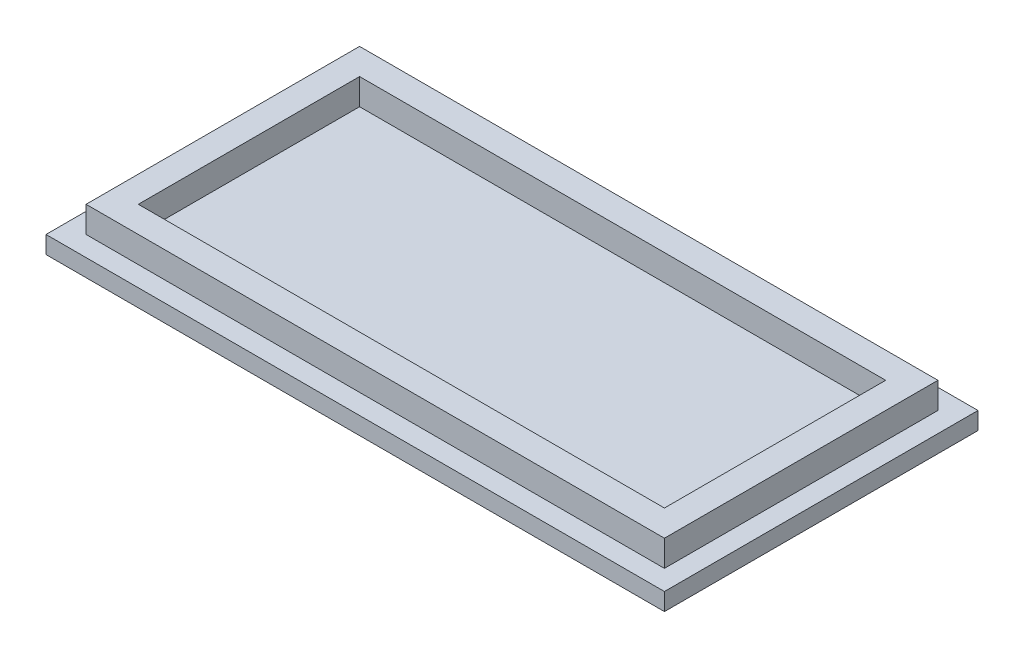
SolidWorks part; units mm, degrees
ref_plane "Piano frontale" through (0, 0, 0) normal (0, 0, 1) x (1, 0, 0)
ref_plane "Piano superiore" through (0, 0, 0) normal (0, 1, 0) x (1, 0, 0)
ref_plane "Piano destro" through (0, 0, 0) normal (1, 0, 0) x (0, 0, -1)
sketch "Schizzo1" plane through (0, 0, 0) normal (0, 1, 0) x (1, 0, 0)
  line L1 (-35.5, -18) -> (35.5, -18)
  line L2 (-35.5, -18) -> (-35.5, 18)
  line L3 (-35.5, 18) -> (35.5, 18)
  line L4 (35.5, -18) -> (35.5, 18)
  line L5 (-35.5, -18) -> (35.5, 18) construction
  line L6 (-35.5, 18) -> (35.5, -18) construction
  point P0 (0, 0)
  dimension "D1" = 71
  dimension "D2" = 36
extrude "Estrusione-Estrusione1" add sketch "Schizzo1" along normal blind 2
sketch "Schizzo2" plane through (0, 2, 0) normal (0, 1, 0) x (1, 0, 0)
  line L1 (-33.2, -15.7) -> (33.2, -15.7)
  line L2 (-33.2, -15.7) -> (-33.2, 15.7)
  line L3 (-33.2, 15.7) -> (33.2, 15.7)
  line L4 (33.2, -15.7) -> (33.2, 15.7)
  line L5 (-33.2, -15.7) -> (33.2, 15.7) construction
  line L6 (-33.2, 15.7) -> (33.2, -15.7) construction
  point P0 (0, 0)
  dimension "D1" = 66.4
  dimension "D2" = 31.4
extrude "Estrusione-Estrusione2" add sketch "Schizzo2" along normal blind 3
sketch "Schizzo3" plane through (0, 0, 0) normal (0, -1, 0) x (1, 0, 0)
  circle A0 centre (0, 0) radius 5
  dimension "D1" = 10
extrude "Estrusione-Estrusione3" add sketch "Schizzo3" along normal blind 5
sketch "Schizzo4" plane through (0, 5, 0) normal (0, 1, 0) x (1, 0, 0)
  line L1 (-30.2, -12.7) -> (30.2, -12.7)
  line L2 (-30.2, -12.7) -> (-30.2, 12.7)
  line L3 (-30.2, 12.7) -> (30.2, 12.7)
  line L4 (30.2, -12.7) -> (30.2, 12.7)
  line L5 (-30.2, -12.7) -> (30.2, 12.7) construction
  line L6 (-30.2, 12.7) -> (30.2, -12.7) construction
  point P0 (0, 0)
  dimension "D1" = 60.4
  dimension "D2" = 25.4
extrude "Taglio-Estrusione1" cut sketch "Schizzo4" against normal blind 3
